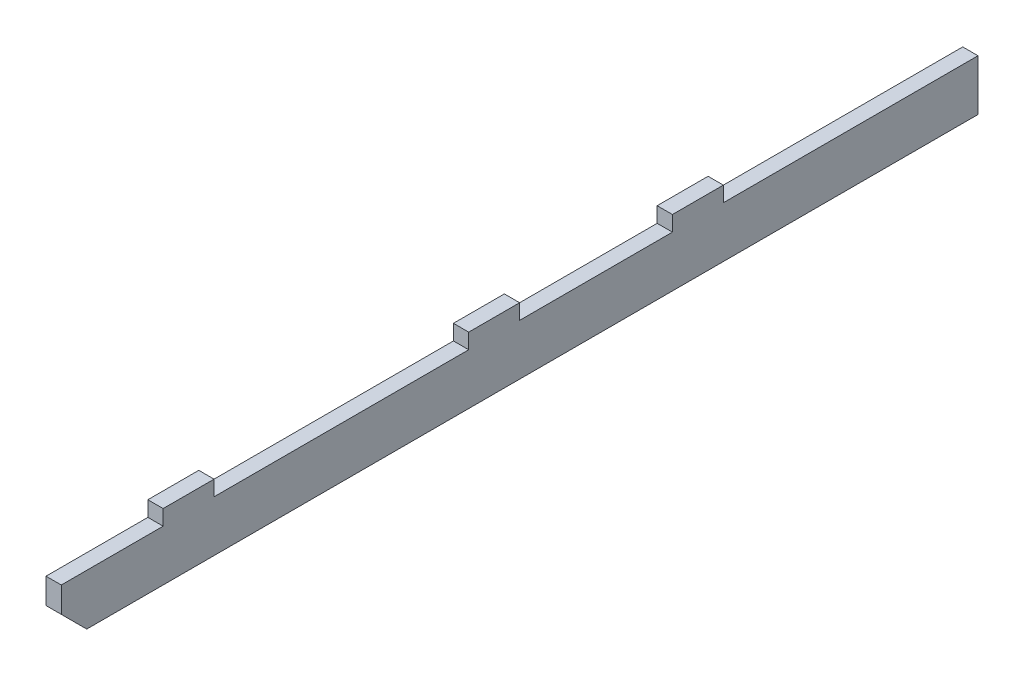
SolidWorks part; units mm, degrees
ref_plane "Front Plane" through (0, 0, 0) normal (0, 0, 1) x (1, 0, 0)
ref_plane "Top Plane" through (0, 0, 0) normal (0, 1, 0) x (1, 0, 0)
ref_plane "Right Plane" through (0, 0, 0) normal (1, 0, 0) x (0, 0, -1)
sketch "Sketch1" plane through (0, 0, 0) normal (1, 0, 0) x (0, 0, -1)
  line L0 (-60, 5) -> (-10, 5)
  line L1 (-90, 5) -> (-70, 5)
  line L2 (-90, 5) -> (-90, -5)
  line L3 (-90, -5) -> (90, -5)
  line L4 (90, 5) -> (90, -5)
  line L5 (-90, 5) -> (90, -5) construction
  line L6 (-90, -5) -> (90, 5) construction
  line L8 (40, 5) -> (40, 8)
  line L9 (40, 8) -> (30, 8)
  line L10 (30, 5) -> (30, 8)
  line L12 (0, 5) -> (0, 8)
  line L13 (0, 8) -> (-10, 8)
  line L14 (-10, 5) -> (-10, 8)
  line L16 (-60, 5) -> (-60, 8)
  line L17 (-60, 8) -> (-70, 8)
  line L18 (-70, 5) -> (-70, 8)
  line L19 (0, 5) -> (30, 5)
  line L20 (40, 5) -> (90, 5)
  point P0 (0, 0)
  dimension "D1" = 10
  dimension "D2" = 50
  dimension "D3" = 10
  dimension "D4" = 3
  dimension "D5" = 3
  dimension "D6" = 30
  dimension "D7" = 10
  dimension "D8" = 10
  dimension "D9" = 3
  dimension "D10" = 50
  dimension "D11" = 180
extrude "Boss-Extrude1" add sketch "Sketch1" along normal blind 3
chamfer "Chamfer1" distance 5 angle 45 1 edges at (1.5, -5, 90)
